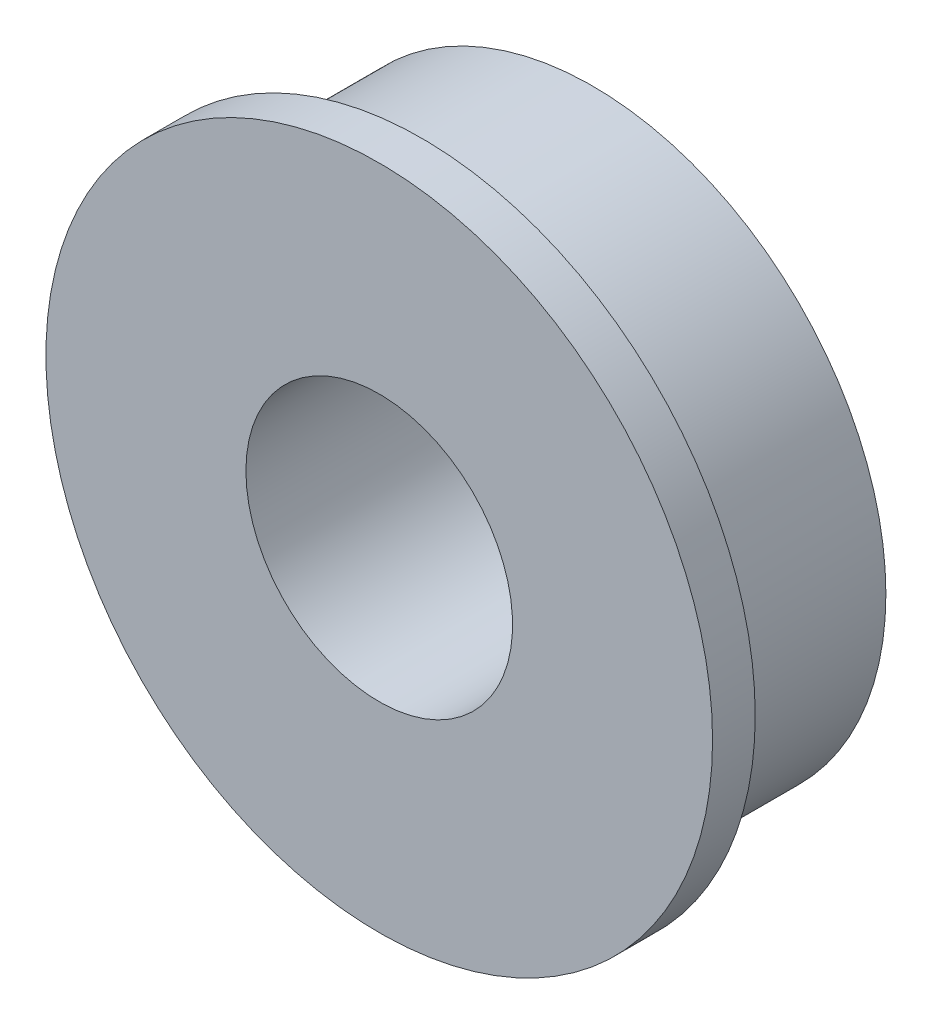
SolidWorks part; units mm, degrees
ref_plane "前视基准面" through (0, 0, 0) normal (0, 0, 1) x (1, 0, 0)
ref_plane "上视基准面" through (0, 0, 0) normal (0, 1, 0) x (1, 0, 0)
ref_plane "右视基准面" through (0, 0, 0) normal (1, 0, 0) x (0, 0, -1)
sketch "草图1" plane through (0, 0, 0) normal (0, 0, 1) x (1, 0, 0)
  circle A0 centre (0, 0) radius 5.5
extrude "凸台-拉伸1" add sketch "草图1" along normal blind 4
sketch "草图2" plane through (0, 0, 4) normal (0, 0, 1) x (1, 0, 0)
  circle A0 centre (0, 0) radius 6.25
extrude "凸台-拉伸2" add sketch "草图2" against normal blind 0.8
sketch "草图3" plane through (0, 0, 0) normal (0, 0, -1) x (-1, 0, 0)
  circle A0 centre (0, 0) radius 2.5
extrude "切除-拉伸1" cut sketch "草图3" against normal through all
